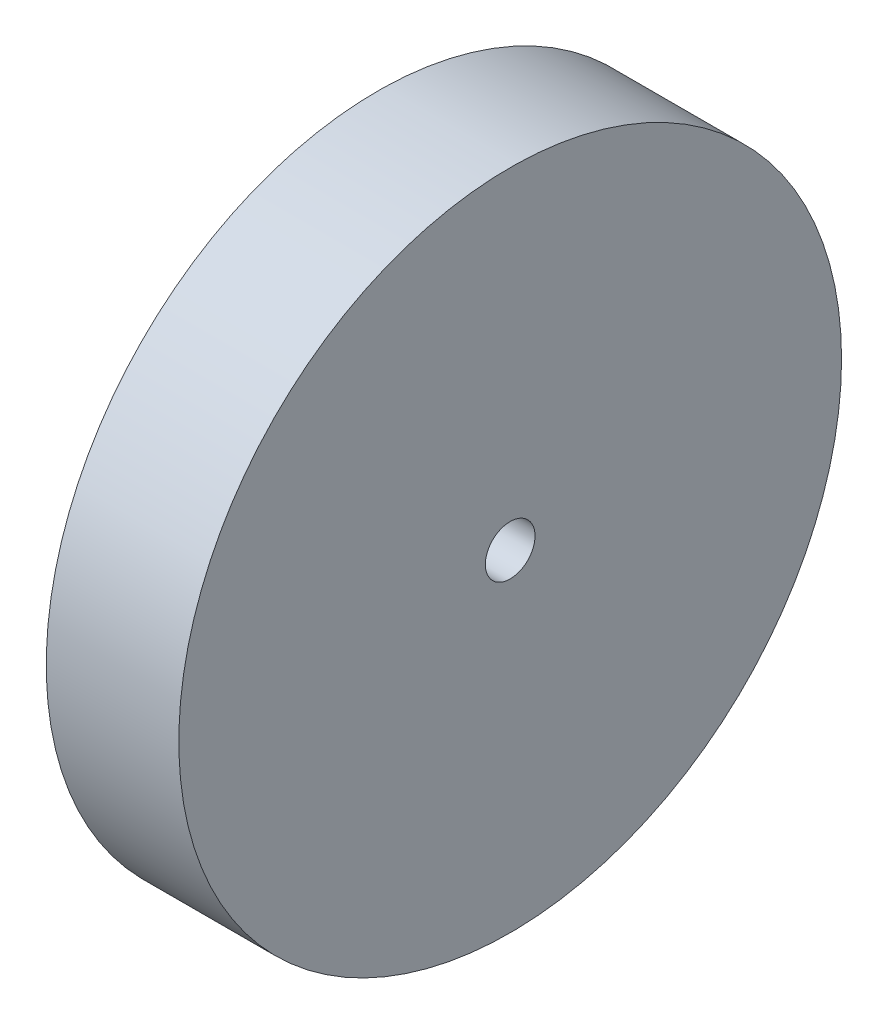
SolidWorks part; units mm, degrees
ref_plane "Front Plane" through (0, 0, 0) normal (0, 0, 1) x (1, 0, 0)
ref_plane "Top Plane" through (0, 0, 0) normal (0, 1, 0) x (1, 0, 0)
ref_plane "Right Plane" through (0, 0, 0) normal (1, 0, 0) x (0, 0, -1)
sketch "Sketch1" plane through (0, 0, 0) normal (1, 0, 0) x (0, 0, -1)
  circle A0 centre (0, 0) radius 127
extrude "Boss-Extrude1" add sketch "Sketch1" along normal blind 50.8
sketch "Sketch2" plane through (50.8, 0, 0) normal (1, 0, 0) x (0, 0, -1)
  circle A0 centre (0, 0) radius 9.525
extrude "Cut-Extrude1" cut sketch "Sketch2" against normal blind 50.8
